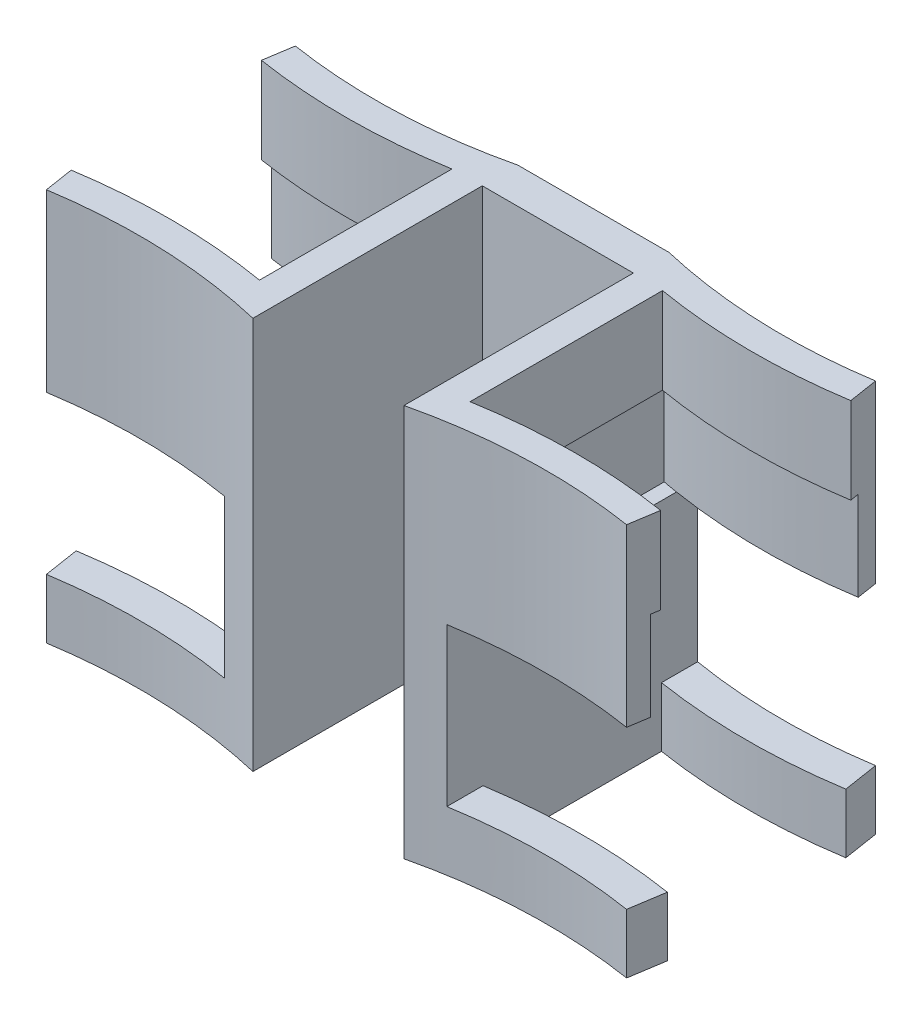
SolidWorks part; units mm, degrees
ref_plane "Front Plane" through (0, 0, 0) normal (0, 0, 1) x (1, 0, 0)
ref_plane "Top Plane" through (0, 0, 0) normal (0, 1, 0) x (1, 0, 0)
ref_plane "Right Plane" through (0, 0, 0) normal (1, 0, 0) x (0, 0, -1)
sketch "Sketch1" plane through (0, 0, 0) normal (0, 1, 0) x (1, 0, 0)
  line L0 (-6, -1.2833) -> (-6, -31.2833)
  line L1 (0, 0) -> (0, -38.5665)
  line L2 (-37, -1.2833) -> (-36.07, 4.6442)
  line L3 (-37, -31.2833) -> (-36.07, -37.2107)
  line L4 (0, 6) -> (25.4, 6)
  line L5 (31.4, -1.2833) -> (31.4, -31.2833)
  line L6 (25.4, 0) -> (25.4, -38.5665)
  line L7 (62.4, -1.2833) -> (61.47, 4.6442)
  line L8 (62.4, -31.2833) -> (61.47, -37.2107)
  line L9 (0, 0) -> (25.4, 0)
  line L10 (0, 6) -> (0, -38.5665) construction
  line L11 (25.4, 6) -> (25.4, -38.5665) construction
  arc A0 (-6, -1.2833) -> (-37, -1.2833) centre (-21.5, 97.5082) cw
  arc A1 (-6, -31.2833) -> (-37, -31.2833) centre (-21.5, -130.0747) ccw
  arc A2 (0, 6) -> (-36.07, 4.6442) centre (-21.5, 97.5082) cw
  arc A3 (0, -38.5665) -> (-36.07, -37.2107) centre (-21.5, -130.0747) ccw
  arc A4 (31.4, -1.2833) -> (62.4, -1.2833) centre (46.9, 97.5082) ccw
  arc A5 (31.4, -31.2833) -> (62.4, -31.2833) centre (46.9, -130.0747) cw
  arc A6 (25.4, 6) -> (61.47, 4.6442) centre (46.9, 97.5082) ccw
  arc A7 (25.4, -38.5665) -> (61.47, -37.2107) centre (46.9, -130.0747) cw
  dimension "D1" = 100
  dimension "D2" = 31
  dimension "D3" = 30
  dimension "D4" = 31
  dimension "D5" = 31
  dimension "D7" = 31
  dimension "D9" = 30
  dimension "D10" = 25.4
  dimension "D11" = 6
  dimension "D6" = 6
  dimension "D8" = 6
extrude "Boss-Extrude1" add sketch "Sketch1" along normal blind 66
sketch "Sketch2" plane through (0, 66, 0) normal (0, 1, 0) x (1, 0, 0)
  line L12 (-6, -1.2833) -> (-6, -31.2833)
  line L13 (31.4, -1.2833) -> (31.4, -31.2833)
  line L14 (62.4, -1.2833) -> (62.4, -31.2833)
  line L15 (-37, -1.2833) -> (-37, -31.2833)
  line L16 (-5, -0.1071) -> (-5, -32.4594)
  line L17 (-38, -0.1071) -> (-38, -32.4594)
  line L18 (63.4, -0.1071) -> (63.4, -32.4594)
  line L19 (30.4, -0.1071) -> (30.4, -32.4594)
  arc A24 (-37, -1.2833) -> (-6, -1.2833) centre (-21.5, 97.5082) ccw
  arc A25 (-37, -31.2833) -> (-6, -31.2833) centre (-21.5, -130.0747) cw
  arc A26 (31.4, -1.2833) -> (62.4, -1.2833) centre (46.9, 97.5082) ccw
  arc A27 (31.4, -31.2833) -> (62.4, -31.2833) centre (46.9, -130.0747) cw
  arc A28 (62.4, -31.2833) -> (31.4, -31.2833) centre (46.9, -130.0747) ccw construction
  arc A29 (-38, -0.1071) -> (-5, -0.1071) centre (-21.5, 97.5082) ccw
  arc A30 (-38, -32.4594) -> (-5, -32.4594) centre (-21.5, -130.0747) cw
  arc A31 (30.4, -32.4594) -> (63.4, -32.4594) centre (46.9, -130.0747) cw
  arc A32 (30.4, -0.1071) -> (63.4, -0.1071) centre (46.9, 97.5082) ccw
  dimension "D1" = 100
  dimension "D2" = 1
  dimension "D3" = 1
extrude "Cut-Extrude1" cut sketch "Sketch2" against normal blind 15
sketch "Sketch3" plane through (0, 51, 0) normal (0, 1, 0) x (1, 0, 0)
  line L0 (-37, -1.2833) -> (-37, -31.2833)
  line L1 (-6, -1.2833) -> (-6, -31.2833)
  line L2 (31.4, -1.2833) -> (31.4, -31.2833)
  line L3 (62.4, -1.2833) -> (62.4, -31.2833)
  line L4 (-3.5, 1.6841) -> (-3.5, -34.2506)
  line L5 (-39.5, 1.6841) -> (-39.5, -34.2506)
  line L6 (64.9, 1.6841) -> (64.9, -34.2506)
  line L7 (28.9, 1.6841) -> (28.9, -34.2506)
  arc A0 (-37, -1.2833) -> (-6, -1.2833) centre (-21.5, 97.5082) ccw
  arc A1 (-37, -31.2833) -> (-6, -31.2833) centre (-21.5, -130.0747) cw
  arc A2 (31.4, -1.2833) -> (62.4, -1.2833) centre (46.9, 97.5082) ccw
  arc A3 (31.4, -31.2833) -> (62.4, -31.2833) centre (46.9, -130.0747) cw
  arc A4 (-39.5, -34.2506) -> (-3.5, -34.2506) centre (-21.5, -130.0747) cw
  arc A5 (-39.5, 1.6841) -> (-3.5, 1.6841) centre (-21.5, 97.5082) ccw
  arc A6 (28.9, -34.2506) -> (64.9, -34.2506) centre (46.9, -130.0747) cw
  arc A7 (28.9, 1.6841) -> (64.9, 1.6841) centre (46.9, 97.5082) ccw
  dimension "D1" = 100
  dimension "D2" = 2.5
extrude "Cut-Extrude2" cut sketch "Sketch3" against normal blind 15 from offset 0.5
sketch "Sketch4" plane through (-6, 0, 0) normal (-1, 0, 0) x (0, 0, 1)
  line L0 (-6, 36.5) -> (38.5665, 36.5)
  line L1 (31.2833, 36.5) -> (1.2833, 36.5) construction
  line L2 (38.5665, 36.5) -> (38.5665, 10)
  line L3 (38.5665, 10) -> (-6, 10)
  line L4 (-6, 10) -> (-6, 36.5)
  line L5 (-6, 66) -> (-6, 0) construction
  line L6 (38.5665, 66) -> (38.5665, 0) construction
  line L7 (1.2833, 0) -> (31.2833, 0) construction
  dimension "D1" = 10
extrude "Cut-Extrude3" cut sketch "Sketch4" along normal through all
sketch "Sketch5" plane through (31.4, 0, 0) normal (1, 0, 0) x (0, 0, -1)
  line L0 (-38.5665, 36.5) -> (6, 36.5)
  line L1 (6, 36.5) -> (6, 10)
  line L2 (6, 10) -> (-38.5665, 10)
  line L3 (-38.5665, 10) -> (-38.5665, 36.5)
  line L4 (-1.2833, 36.5) -> (-31.2833, 36.5) construction
  line L5 (-38.5665, 66) -> (-38.5665, 0) construction
  line L6 (6, 66) -> (6, 0) construction
  line L7 (-31.2833, 0) -> (-1.2833, 0) construction
  dimension "D1" = 10
extrude "Cut-Extrude4" cut sketch "Sketch5" along normal through all
